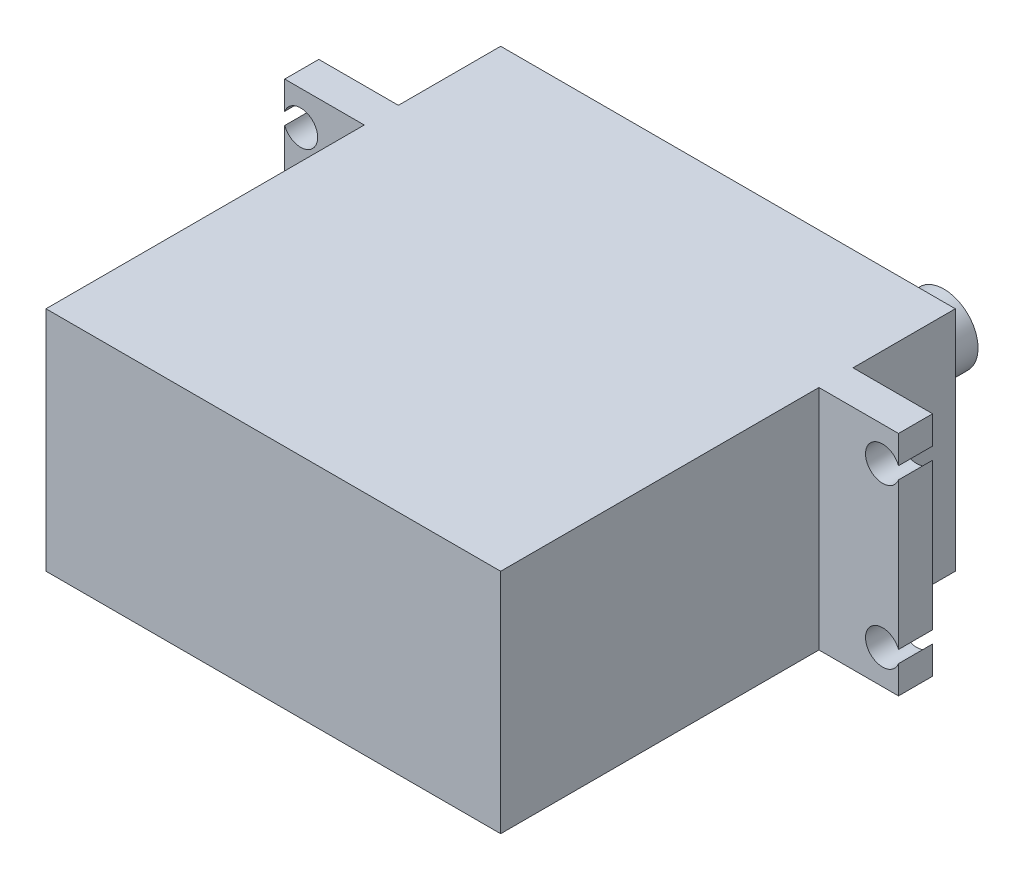
SolidWorks part; units mm, degrees
ref_plane "Plan de face" through (0, 0, 0) normal (0, 0, 1) x (1, 0, 0)
ref_plane "Plan de dessus" through (0, 0, 0) normal (0, 1, 0) x (1, 0, 0)
ref_plane "Plan de droite" through (0, 0, 0) normal (1, 0, 0) x (0, 0, -1)
sketch "Esquisse1" plane through (0, 0, 0) normal (0, 0, 1) x (1, 0, 0)
  line L1 (0, 0) -> (40, 0)
  line L2 (0, 0) -> (0, 20)
  line L3 (0, 20) -> (40, 20)
  line L4 (40, 0) -> (40, 20)
  dimension "D1" = 40
  dimension "D2" = 20
extrude "Boss.-Extru.1" add sketch "Esquisse1" along normal blind 40
sketch "Esquisse3" plane through (40, 0, 0) normal (1, 0, 0) x (0, 0, -1)
  line L0 (-40, 20) -> (0, 20) construction
  line L1 (-9, 20) -> (-12, 20)
  line L2 (-9, 20) -> (-9, 0)
  line L3 (-9, 0) -> (-12, 0)
  line L4 (-12, 20) -> (-12, 0)
  line L5 (-40, 0) -> (0, 0) construction
  line L6 (0, 0) -> (0, 20) construction
  dimension "D1" = 3
  dimension "D2" = 9
extrude "Boss.-Extru.2" add sketch "Esquisse3" along normal blind 7
sketch "Esquisse4" plane through (0, 0, 0) normal (-1, 0, 0) x (0, 0, 1)
  line L0 (40, 20) -> (0, 20) construction
  line L1 (9, 20) -> (12, 20)
  line L2 (9, 20) -> (9, 0)
  line L3 (9, 0) -> (12, 0)
  line L4 (12, 20) -> (12, 0)
  line L5 (40, 0) -> (0, 0) construction
  line L6 (0, 20) -> (0, 0) construction
  dimension "D1" = 9
  dimension "D2" = 12
extrude "Boss.-Extru.3" add sketch "Esquisse4" along normal blind 7
sketch "Esquisse5" plane through (0, 0, 9) normal (0, 0, -1) x (-1, 0, 0)
  line L0 (-47, 20) -> (-40, 20) construction
  line L1 (-47, 0) -> (-40, 0) construction
  line L2 (7, 0) -> (0, 0) construction
  line L3 (7, 20) -> (0, 20) construction
  line L4 (-40, 0) -> (-40, 20) construction
  line L5 (0, 20) -> (0, 0) construction
  circle A0 centre (-45.6, 17) radius 1.5
  circle A1 centre (-45.6, 3) radius 1.5
  circle A2 centre (5.6, 17) radius 1.5
  circle A3 centre (5.6, 3) radius 1.5
  dimension "D5" = 3
  dimension "D6" = 3
  dimension "D7" = 3
  dimension "D8" = 3
  dimension "D1" = 3
  dimension "D2" = 3
  dimension "D3" = 3
  dimension "D4" = 3
  dimension "D9" = 5.6
  dimension "D10" = 5.6
  dimension "D11" = 5.6
  dimension "D12" = 5.6
extrude "Enlèv. mat.-Extru.3" cut sketch "Esquisse5" against normal blind 7
sketch "Esquisse6" plane through (0, 0, 0) normal (0, 0, -1) x (-1, 0, 0)
  line L0 (-40, 0) -> (-40, 20) construction
  line L1 (0, 0) -> (-40, 0) construction
  circle A0 centre (-31, 10) radius 3
  point P4 (-40, 10)
  dimension "D2" = 6
  dimension "D1" = 9
  dimension "D3" = 10
extrude "Boss.-Extru.4" add sketch "Esquisse6" along normal blind 8
